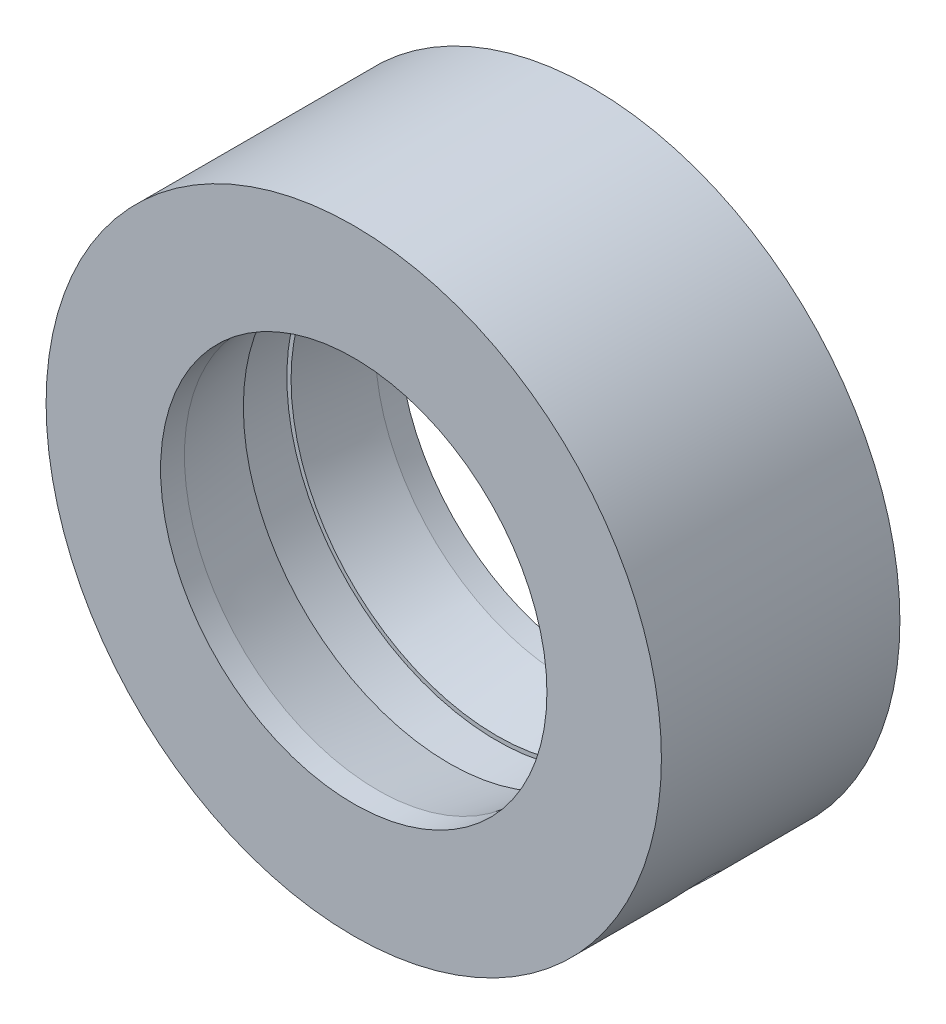
SolidWorks part; units mm, degrees
ref_plane "Front Plane" through (0, 0, 0) normal (0, 0, 1) x (1, 0, 0)
ref_plane "Top Plane" through (0, 0, 0) normal (0, 1, 0) x (1, 0, 0)
ref_plane "Right Plane" through (0, 0, 0) normal (1, 0, 0) x (0, 0, -1)
sketch "Sketch1" plane through (0, 0, 0) normal (0, 0, 1) x (1, 0, 0)
  line L0 (-26.538, 0) -> (73.462, 0) construction
  line L2 (-26.538, 0) -> (23.462, 50) construction
  line L3 (23.462, 50) -> (73.462, 0) construction
  line L4 (-14.6464, 5) -> (61.5704, 5)
  line L5 (-14.6464, -5) -> (61.5704, -5)
  line L6 (-21.6649, 11.9442) -> (11.5178, 45.1269)
  line L7 (18.5889, 38.0558) -> (-14.5938, 4.8731)
  line L8 (28.3351, 38.0558) -> (61.5178, 4.8731)
  line L9 (35.4062, 45.1269) -> (68.5889, 11.9442)
  circle A0 centre (23.462, 50) radius 8.1
  circle A1 centre (73.462, 0) radius 8.1
  circle A2 centre (-26.538, 0) radius 8.1
  circle A3 centre (-26.538, 0) radius 12.9
  circle A4 centre (23.462, 50) radius 12.9
  circle A5 centre (73.462, 0) radius 12.9
  dimension "D1" = 16.2
  dimension "D2" = 16.2
  dimension "D3" = 16.2
  dimension "D4" = 45
  dimension "D5" = 45
  dimension "D6" = 100
  dimension "D7" = 4.8
  dimension "D8" = 4.8
  dimension "D9" = 4.8
  dimension "D10" = 5
  dimension "D11" = 5
  dimension "D12" = 5
  dimension "D13" = 5
  dimension "D14" = 5
  dimension "D15" = 5
extrude "Boss-Extrude1" add sketch "Sketch1" along normal blind 8 contours A3 A2 | A4 L6 A3 L4 L7 | A3 L7 L4 | A5 L8 L4 L7 A3 L5 | A4 A0 | A5 L9 A4 L8 L4 | A5 A1 | A5 L4 L8
sketch3d "3DSketch1" plane through (0, 0, 0) normal (0, 0, 1) x (1, 0, 0)
  dimension "D1" = 4
sketch "Sketch3" plane through (0, 0, 4) normal (0, 0, 1) x (1, 0, 0)
  circle A0 centre (-26.538, 0) radius 8.8053
  circle A1 centre (23.462, 50) radius 8.8053
  circle A2 centre (73.462, 0) radius 8.8053
  circle A3 centre (-26.538, 0) radius 8.1 construction
  circle A4 centre (23.462, 50) radius 8.1 construction
  circle A5 centre (73.462, 0) radius 8.1 construction
  dimension "D1" = 0.7053
  dimension "D2" = 0.7053
  dimension "D3" = 0.7053
extrude "Cut-Extrude1" cut sketch "Sketch3" against normal blind 1 and the other way blind 1 contours A1 | A0 | A2
sketch3d "3DSketch2" plane through (0, 0, 0) normal (0, 0, 1) x (1, 0, 0)
sketch3d "3DSketch3" plane through (0, 0, 0) normal (0, 0, 1) x (1, 0, 0)
  dimension "D1" = 26
sketch "Sketch4" plane through (0, 63.1, 0) normal (0, -1, 0) x (-1, 0, 0)
  line L0 (-41.8, -4) -> (41.8, -4) construction
  line L1 (-86.362, 0) -> (-86.362, -8) construction
  line L4 (-36.362, -8) -> (-68.5889, -8)
  line L5 (-36.362, -8) -> (-68.5889, -8)
  line L6 (-68.5889, -8) -> (-86.362, -8)
  line L7 (-68.5889, -8) -> (-86.362, -8)
  line L8 (-86.362, -8) -> (-86.362, 0)
  line L9 (-86.362, -8) -> (-86.362, 0)
  line L10 (-86.362, 0) -> (-68.5889, 0)
  line L11 (-86.362, 0) -> (-68.5889, 0)
  line L12 (-68.5889, 0) -> (-36.362, 0)
  line L13 (-68.5889, 0) -> (-36.362, 0)
  line L14 (-36.362, 0) -> (-10.562, 0)
  line L15 (-36.362, 0) -> (-10.562, 0)
  line L16 (-10.562, 0) -> (21.6649, 0)
  line L17 (-10.562, 0) -> (21.6649, 0)
  line L18 (21.6649, 0) -> (39.438, 0)
  line L19 (21.6649, 0) -> (39.438, 0)
  line L20 (39.438, 0) -> (39.438, -8)
  line L21 (39.438, 0) -> (39.438, -8)
  line L22 (39.438, -8) -> (21.6649, -8)
  line L23 (39.438, -8) -> (21.6649, -8)
  line L24 (21.6649, -8) -> (-10.562, -8)
  line L25 (21.6649, -8) -> (-10.562, -8)
  line L26 (-10.562, -8) -> (-36.362, -8)
  line L27 (-10.562, -8) -> (-36.362, -8)
  circle A0 centre (-23.512, -4) radius 1
  dimension "D1" = 2
  dimension "D2" = 62.85
  dimension "D3" = 125.8
extrude "Cut-Extrude2" cut sketch "Sketch4" along normal blind 6 contours A0
fillet "Fillet1" radius 3 4 edges at (-14.4669, 5, 4) (18.5889, 38.0558, 4) (28.3351, 38.0558, 4) (61.3909, 5, 4)
fillet "Fillet2" radius 5 6 edges at (68.5889, 11.9442, 4) (35.4062, 45.1269, 4) (11.5178, 45.1269, 4) (-21.6649, 11.9442, 4) (-14.6464, -5, 4) (61.5704, -5, 4)
sketch3d "3DSketch4" plane through (0, 0, 0) normal (0, 0, 1) x (1, 0, 0)
sketch3d "3DSketch5" plane through (0, 0, 0) normal (0, 0, 1) x (1, 0, 0)
  dimension "D1" = 26
sketch "Sketch5" plane through (45.9941, -45.9941, 0) normal (-0.7071, 0.7071, 0) x (0, 0, 1)
  line L0 (8, -31.6652) -> (8, -8.066) construction
  line L1 (8, 43.8455) -> (8, 60.0455) construction
  line L2 (8, 43.8455) -> (8, 60.0455)
  line L7 (8, 64.8455) -> (0, 64.8455) construction
  line L8 (8, 64.8455) -> (0, 64.8455)
  circle A0 centre (4, 51.9955) radius 1
  dimension "D1" = 2
  dimension "D2" = 4
  dimension "D3" = 8.15
  dimension "D4" = 16.2
  dimension "D5" = 8
extrude "Cut-Extrude3" cut sketch "Sketch5" along normal blind 10 contours A0
draft "Draft4" type of draft neutral plane draft angle 10 faces to draft 3 face at (-18.438, 0, 5) face at (31.562, 50, 5) face at (81.562, 0, 5) neutral plane through (0, 0, 8) neutral plane normal (0, 0, 1) reverse direction yes parameters "D1"=10
draft "Draft6" type of draft neutral plane draft angle 10 faces to draft 3 face at (-18.438, 0, 0) face at (81.562, 0, 0) face at (31.562, 50, 0) neutral plane through (0, 0, 0) neutral plane normal (0, 0, -1) reverse direction yes parameters "D1"=10
sketch3d "3DSketch6" plane through (0, 0, 0) normal (0, 0, 1) x (1, 0, 0)
sketch3d "3DSketch8" plane through (0, 0, 0) normal (0, 0, 1) x (1, 0, 0)
  dimension "D1" = 26
sketch "Sketch6" plane through (-22.5321, -22.5321, 0) normal (0.7071, 0.7071, 0) x (0, 0, -1)
  line L0 (-8, 31.6652) -> (-8, 5.8652) construction
  line L1 (0, 31.6652) -> (-8, 31.6652) construction
  line L2 (0, 31.6652) -> (-8, 31.6652)
  line L3 (0, 10.6652) -> (0, 26.8652) construction
  line L4 (0, 10.6652) -> (0, 26.8652)
  circle A0 centre (-4, 18.7152) radius 1
  dimension "D1" = 2
  dimension "D2" = 4
  dimension "D4" = 16.2
  dimension "D3" = 8
  dimension "D5" = 8.15
extrude "Cut-Extrude4" cut sketch "Sketch6" along normal blind 10 contours A0
sketch "Sketch7" plane through (0, 0, 8) normal (0, 0, 1) x (1, 0, 0)
  line L2 (-7.2243, 5) -> (54.1483, 5) construction
  line L5 (17.2813, 36.7482) -> (-9.3456, 10.1213) construction
  line L10 (29.6427, 36.7482) -> (56.2696, 10.1213) construction
  line L11 (66.4997, 14.0334) -> (37.4954, 43.0377)
  line L12 (9.4286, 43.0377) -> (-19.5757, 14.0334)
  line L13 (-11.6918, -5) -> (58.6158, -5)
  line L14 (66.4997, 14.0334) -> (37.4954, 43.0377)
  line L15 (9.4286, 43.0377) -> (-19.5757, 14.0334)
  line L16 (-11.6918, -5) -> (58.6158, -5)
  line L17 (-7.2243, 5) -> (54.1483, 5)
  line L18 (17.2813, 36.7482) -> (-9.3456, 10.1213)
  line L19 (29.6427, 36.7482) -> (56.2696, 10.1213)
  circle A36 centre (-26.538, 0) radius 8.1 construction
  arc A37 (-9.3456, 10.1213) -> (-7.2243, 5) centre (-7.2243, 8) ccw construction
  arc A38 (54.1483, 5) -> (56.2696, 10.1213) centre (54.1483, 8) ccw construction
  circle A39 centre (73.462, 0) radius 8.1 construction
  circle A40 centre (23.462, 50) radius 8.1 construction
  arc A41 (29.6427, 36.7482) -> (26.7554, 37.5275) centre (27.5214, 34.6269) ccw construction
  arc A42 (20.1685, 37.5275) -> (26.7554, 37.5275) centre (23.462, 50) ccw construction
  arc A43 (20.1685, 37.5275) -> (17.2813, 36.7482) centre (19.4026, 34.6269) ccw construction
  circle A44 centre (-26.538, 0) radius 8.1
  arc A45 (36.1234, 47.5304) -> (37.4954, 43.0377) centre (41.0309, 46.5732) ccw
  arc A46 (36.1234, 47.5304) -> (10.8006, 47.5304) centre (23.462, 50) ccw
  arc A47 (9.4286, 43.0377) -> (10.8006, 47.5304) centre (5.8931, 46.5732) ccw
  arc A48 (-24.0684, 12.6614) -> (-19.5757, 14.0334) centre (-23.1112, 17.5689) ccw
  arc A49 (-24.0684, 12.6614) -> (-15.8388, -7.2067) centre (-26.538, 0) ccw
  arc A50 (-11.6918, -5) -> (-15.8388, -7.2067) centre (-11.6918, -10) ccw
  arc A51 (62.7628, -7.2067) -> (58.6158, -5) centre (58.6158, -10) ccw
  arc A52 (62.7628, -7.2067) -> (70.9924, 12.6614) centre (73.462, 0) ccw
  arc A53 (66.4997, 14.0334) -> (70.9924, 12.6614) centre (70.0352, 17.5689) ccw
  arc A54 (36.1234, 47.5304) -> (37.4954, 43.0377) centre (41.0309, 46.5732) ccw
  arc A55 (36.1234, 47.5304) -> (10.8006, 47.5304) centre (23.462, 50) ccw
  arc A56 (9.4286, 43.0377) -> (10.8006, 47.5304) centre (5.8931, 46.5732) ccw
  arc A57 (-24.0684, 12.6614) -> (-19.5757, 14.0334) centre (-23.1112, 17.5689) ccw
  arc A58 (-24.0684, 12.6614) -> (-15.8388, -7.2067) centre (-26.538, 0) ccw
  arc A59 (-11.6918, -5) -> (-15.8388, -7.2067) centre (-11.6918, -10) ccw
  arc A60 (62.7628, -7.2067) -> (58.6158, -5) centre (58.6158, -10) ccw
  arc A61 (62.7628, -7.2067) -> (70.9924, 12.6614) centre (73.462, 0) ccw
  arc A62 (66.4997, 14.0334) -> (70.9924, 12.6614) centre (70.0352, 17.5689) ccw
  arc A63 (-9.3456, 10.1213) -> (-7.2243, 5) centre (-7.2243, 8) ccw
  arc A64 (54.1483, 5) -> (56.2696, 10.1213) centre (54.1483, 8) ccw
  circle A65 centre (73.462, 0) radius 8.1
  circle A66 centre (23.462, 50) radius 8.1
  arc A67 (29.6427, 36.7482) -> (26.7554, 37.5275) centre (27.5214, 34.6269) ccw
  arc A68 (20.1685, 37.5275) -> (26.7554, 37.5275) centre (23.462, 50) ccw
  arc A69 (20.1685, 37.5275) -> (17.2813, 36.7482) centre (19.4026, 34.6269) ccw
  dimension "D1" = 0
extrude "Boss-Extrude3" add sketch "Sketch7" along normal blind 1
sketch "Sketch11" plane through (0, 0, 0) normal (0, 0, -1) x (-1, 0, 0)
  line L0 (-29.6427, 36.7482) -> (-56.2696, 10.1213) construction
  line L1 (7.2243, 5) -> (-54.1483, 5) construction
  line L2 (-17.2813, 36.7482) -> (9.3456, 10.1213) construction
  line L3 (-37.4954, 43.0377) -> (-66.4997, 14.0334)
  line L4 (-58.6158, -5) -> (11.6918, -5)
  line L5 (19.5757, 14.0334) -> (-9.4286, 43.0377)
  line L6 (-37.4954, 43.0377) -> (-66.4997, 14.0334)
  line L7 (-58.6158, -5) -> (11.6918, -5)
  line L8 (19.5757, 14.0334) -> (-9.4286, 43.0377)
  line L9 (-17.2813, 36.7482) -> (9.3456, 10.1213)
  line L10 (7.2243, 5) -> (-54.1483, 5)
  line L11 (-29.6427, 36.7482) -> (-56.2696, 10.1213)
  circle A0 centre (-23.462, 50) radius 8.1 construction
  circle A1 centre (-73.462, 0) radius 8.1
  circle A2 centre (-73.462, 0) radius 8.1
  circle A3 centre (-23.462, 50) radius 8.1
  circle A4 centre (26.538, 0) radius 8.1 construction
  circle A5 centre (26.538, 0) radius 8.1
  arc A6 (-17.2813, 36.7482) -> (-20.1685, 37.5275) centre (-19.4026, 34.6269) ccw construction
  arc A7 (-26.7554, 37.5275) -> (-20.1685, 37.5275) centre (-23.462, 50) ccw construction
  arc A8 (-26.7554, 37.5275) -> (-29.6427, 36.7482) centre (-27.5214, 34.6269) ccw construction
  arc A9 (-56.2696, 10.1213) -> (-54.1483, 5) centre (-54.1483, 8) ccw construction
  arc A10 (7.2243, 5) -> (9.3456, 10.1213) centre (7.2243, 8) ccw construction
  arc A11 (-10.8006, 47.5304) -> (-36.1234, 47.5304) centre (-23.462, 50) ccw
  arc A12 (-37.4954, 43.0377) -> (-36.1234, 47.5304) centre (-41.0309, 46.5732) ccw
  arc A13 (-70.9924, 12.6614) -> (-66.4997, 14.0334) centre (-70.0352, 17.5689) ccw
  arc A14 (-70.9924, 12.6614) -> (-62.7628, -7.2067) centre (-73.462, 0) ccw
  arc A15 (-58.6158, -5) -> (-62.7628, -7.2067) centre (-58.6158, -10) ccw
  arc A16 (15.8388, -7.2067) -> (11.6918, -5) centre (11.6918, -10) ccw
  arc A17 (15.8388, -7.2067) -> (24.0684, 12.6614) centre (26.538, 0) ccw
  arc A18 (19.5757, 14.0334) -> (24.0684, 12.6614) centre (23.1112, 17.5689) ccw
  arc A19 (-10.8006, 47.5304) -> (-9.4286, 43.0377) centre (-5.8931, 46.5732) ccw
  arc A20 (-10.8006, 47.5304) -> (-36.1234, 47.5304) centre (-23.462, 50) ccw
  arc A21 (-37.4954, 43.0377) -> (-36.1234, 47.5304) centre (-41.0309, 46.5732) ccw
  arc A22 (-70.9924, 12.6614) -> (-66.4997, 14.0334) centre (-70.0352, 17.5689) ccw
  arc A23 (-70.9924, 12.6614) -> (-62.7628, -7.2067) centre (-73.462, 0) ccw
  arc A24 (-58.6158, -5) -> (-62.7628, -7.2067) centre (-58.6158, -10) ccw
  arc A25 (15.8388, -7.2067) -> (11.6918, -5) centre (11.6918, -10) ccw
  arc A26 (15.8388, -7.2067) -> (24.0684, 12.6614) centre (26.538, 0) ccw
  arc A27 (19.5757, 14.0334) -> (24.0684, 12.6614) centre (23.1112, 17.5689) ccw
  arc A28 (-10.8006, 47.5304) -> (-9.4286, 43.0377) centre (-5.8931, 46.5732) ccw
  arc A29 (7.2243, 5) -> (9.3456, 10.1213) centre (7.2243, 8) ccw
  arc A30 (-56.2696, 10.1213) -> (-54.1483, 5) centre (-54.1483, 8) ccw
  arc A31 (-26.7554, 37.5275) -> (-29.6427, 36.7482) centre (-27.5214, 34.6269) ccw
  arc A32 (-26.7554, 37.5275) -> (-20.1685, 37.5275) centre (-23.462, 50) ccw
  arc A33 (-17.2813, 36.7482) -> (-20.1685, 37.5275) centre (-19.4026, 34.6269) ccw
  dimension "D1" = 0
  dimension "D2" = 0
extrude "Boss-Extrude4" add sketch "Sketch11" along normal blind 1
sketch "Sketch12" plane through (0, 0, -1) normal (0, 0, -1) x (-1, 0, 0)
  circle A0 centre (-73.462, 0) radius 12.9
  arc A1 (-70.9924, 12.6614) -> (-62.7628, -7.2067) centre (-73.462, 0) ccw construction
extrude "Cut-Extrude5" cut sketch "Sketch12" against normal through all flip side to cut
equation "\"D2@Sketch1\"=\"D1@Sketch1\""
equation "\"D3@Sketch1\"=\"D1@Sketch1\""
equation "\"D5@Sketch1\"=\"D4@Sketch1\""
equation "\"D8@Sketch1\"=\"D7@Sketch1\""
equation "\"D9@Sketch1\"=\"D7@Sketch1\""
equation "\"D11@Sketch1\"=\"D10@Sketch1\""
equation "\"D12@Sketch1\"=\"D10@Sketch1\""
equation "\"D13@Sketch1\"=\"D10@Sketch1\""
equation "\"D14@Sketch1\"=\"D13@Sketch1\""
equation "\"D15@Sketch1\"=\"D14@Sketch1\""
equation "\"D2@Sketch3\"=\"D1@Sketch3\""
equation "\"D3@Sketch3\"=\"D1@Sketch3\""
equation "\"D2@Sketch4\"=\"D3@Sketch4\"/2"
equation "\"D3@Sketch5\"=\"D4@Sketch5\"/2"
equation "\"D2@Sketch5\"=\"D5@Sketch5\"/2"
equation "\"D2@Sketch6\"=\"D3@Sketch6\"/2"
equation "\"D5@Sketch6\"=\"D4@Sketch6\"/2"
equation "\"D1@Sketch3\"=4*tan(10)"
equation "\"D7@Sketch1\"=21-\"D1@Sketch1\""
